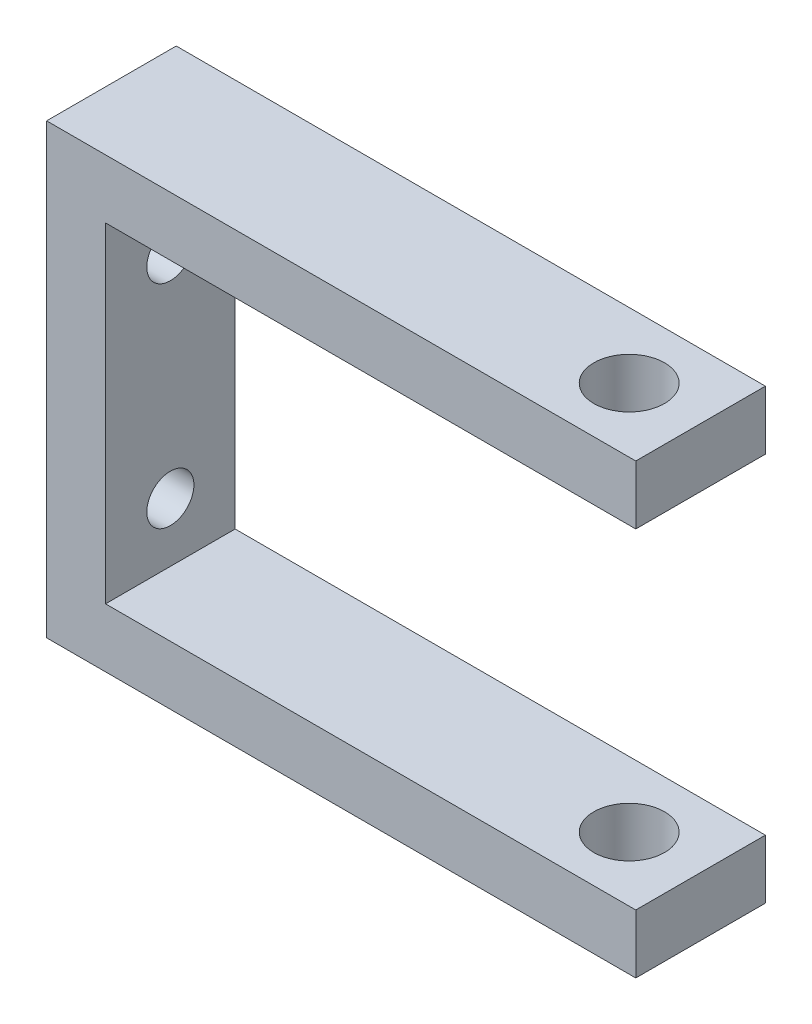
SolidWorks part; units mm, degrees
ref_plane "Front Plane" through (0, 0, 0) normal (0, 0, 1) x (1, 0, 0)
ref_plane "Top Plane" through (0, 0, 0) normal (0, 1, 0) x (1, 0, 0)
ref_plane "Right Plane" through (0, 0, 0) normal (1, 0, 0) x (0, 0, -1)
sketch "Sketch2" plane through (0, 0, 0) normal (0, 0, 1) x (1, 0, 0)
  line L0 (0, 19) -> (-50, 19)
  line L1 (-50, 19) -> (-50, -19)
  line L2 (-50, -19) -> (0, -19)
  line L3 (0, -19) -> (0, -14)
  line L4 (0, -14) -> (-45, -14)
  line L5 (-45, -14) -> (-45, 14)
  line L6 (-45, 14) -> (0, 14)
  line L7 (0, 14) -> (0, 19)
  line L8 (0, 14) -> (0, -14) construction
  line L9 (-5.5, 14) -> (-5.5, -14) construction
  dimension "D1" = 38
  dimension "D2" = 5
  dimension "D3" = 5
  dimension "D4" = 5
  dimension "D5" = 45
  dimension "D6" = 5.5
  dimension "D7" = 14
extrude "Boss-Extrude1" add sketch "Sketch2" along normal blind 11
sketch "Sketch3" plane through (0, 19, 0) normal (0, 1, 0) x (1, 0, 0)
  line L0 (-50, -5.5) -> (0, -5.5) construction
  line L1 (-50, -11) -> (-50, 0) construction
  line L2 (0, -11) -> (0, 0) construction
  line L3 (-6, 0) -> (-6, -5.5595) construction
  line L4 (0, 0) -> (-50, 0) construction
  circle A0 centre (-6, -5.5595) radius 3
  dimension "D1" = 6
  dimension "D2" = 6
extrude "Cut-Extrude1" cut sketch "Sketch3" against normal blind 50
sketch "Sketch4" plane through (-45, 0, 0) normal (1, 0, 0) x (0, 0, -1)
  line L0 (-5.5, 14) -> (-5.5, -14) construction
  line L1 (-11, 14) -> (0, 14) construction
  line L2 (-11, -14) -> (0, -14) construction
  circle A0 centre (-5.5, 9) radius 2
  circle A1 centre (-5.5, -9) radius 2
  point P12 (-3.0713, 9)
  point P13 (-1.1401, -9)
  dimension "D1" = 4
  dimension "D2" = 4
  dimension "D3" = 10
  dimension "D4" = 10
extrude "Cut-Extrude2" cut sketch "Sketch4" against normal blind 10
